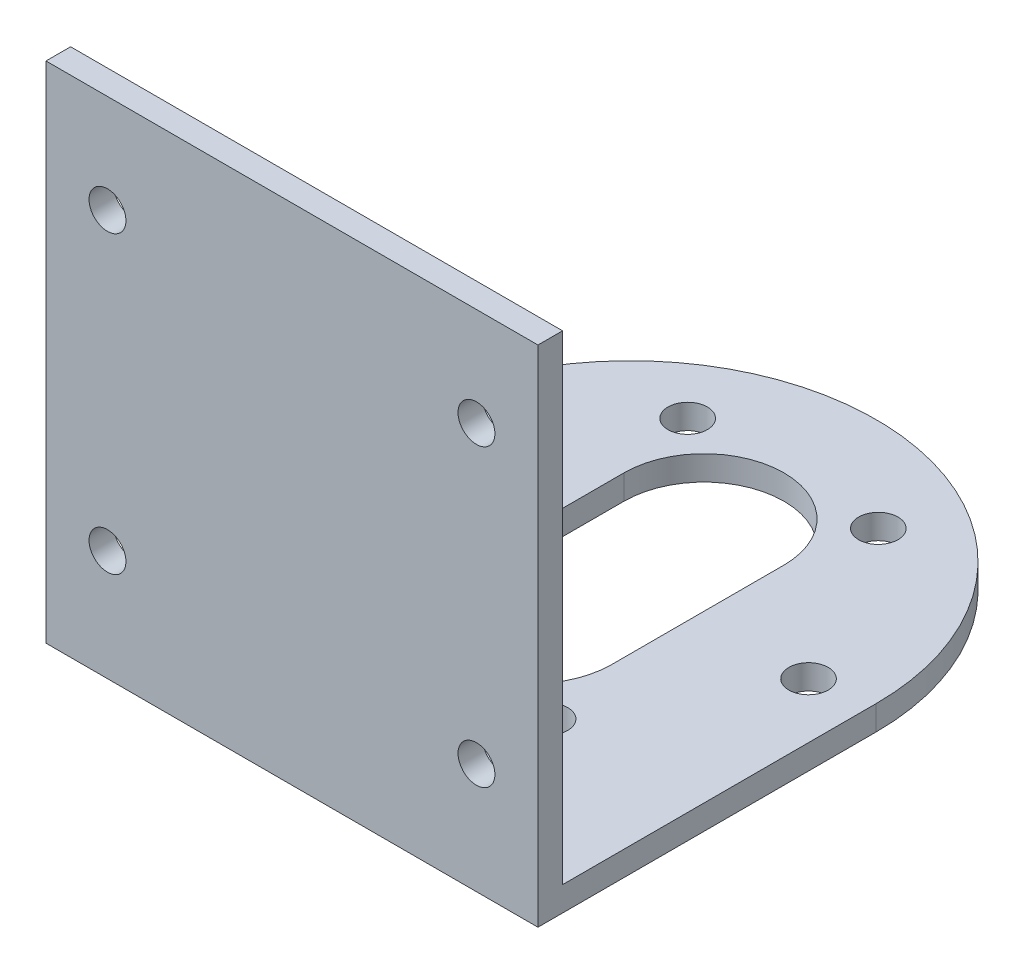
SolidWorks part; units mm, degrees
ref_plane "前视基准面" through (0, 0, 0) normal (0, 0, 1) x (1, 0, 0)
ref_plane "上视基准面" through (0, 0, 0) normal (0, 1, 0) x (1, 0, 0)
ref_plane "右视基准面" through (0, 0, 0) normal (1, 0, 0) x (0, 0, -1)
sketch "草图1" plane through (0, 0, 0) normal (0, 1, 0) x (1, 0, 0)
  line L0 (-21.9582, -2.1643) -> (-21.9582, -29.6643)
  line L1 (-21.9582, -29.6643) -> (18.0418, -29.6643)
  line L2 (18.0418, -29.6643) -> (18.0418, -2.1643)
  line L3 (-1.9582, 17.8357) -> (-57.1523, 17.8357) construction
  line L4 (5.7918, 10.2591) -> (-9.7082, 10.2591) construction
  line L5 (-9.7082, 10.2591) -> (-17.4582, -3.1643) construction
  line L6 (-17.4582, -3.1643) -> (-9.7082, -16.5877) construction
  line L7 (-9.7082, -16.5877) -> (5.7918, -16.5877) construction
  line L8 (5.7918, -16.5877) -> (13.5418, -3.1643) construction
  line L9 (13.5418, -3.1643) -> (5.7918, 10.2591) construction
  line L10 (-1.9582, 3.8357) -> (-1.9582, -10.1643) construction
  line L11 (4.5418, 3.8357) -> (4.5418, -10.1643)
  line L12 (-8.4582, 3.8357) -> (-8.4582, -10.1643)
  arc A0 (18.0418, -2.1643) -> (-21.9582, -2.1643) centre (-1.9582, -2.1643) ccw
  circle A20 centre (-1.9582, -3.1643) radius 15.5 construction
  circle A21 centre (-9.7082, 10.2591) radius 1.6
  circle A22 centre (-17.4582, -3.1643) radius 1.6
  circle A23 centre (-9.7082, -16.5877) radius 1.6
  circle A24 centre (5.7918, -16.5877) radius 1.6
  circle A25 centre (13.5418, -3.1643) radius 1.6
  circle A26 centre (5.7918, 10.2591) radius 1.6
  arc A27 (4.5418, 3.8357) -> (-8.4582, 3.8357) centre (-1.9582, 3.8357) ccw
  arc A28 (-8.4582, -10.1643) -> (4.5418, -10.1643) centre (-1.9582, -10.1643) ccw
  point P10 (-1.9582, -29.6643)
  point P23 (-1.9582, -3.1643)
  dimension "D1" = 40
  dimension "D3" = 31
  dimension "D4" = 26.5
  dimension "D5" = 3.2
  dimension "D6" = 6.5
  dimension "D2" = 47.5
  dimension "D7" = 19.5
extrude "凸台-拉伸1" add sketch "草图1" along normal blind 2
sketch "草图2" plane through (0, 2, 0) normal (0, 1, 0) x (1, 0, 0)
  line L0 (18.0418, -29.6643) -> (18.0418, -2.1643) construction
  line L1 (-21.9582, -29.6643) -> (18.0418, -29.6643)
  line L2 (-21.9582, -29.6643) -> (-21.9582, -27.6643)
  line L3 (-21.9582, -27.6643) -> (18.0418, -27.6643)
  line L4 (18.0418, -29.6643) -> (18.0418, -27.6643)
  dimension "D1" = 2
extrude "凸台-拉伸2" add sketch "草图2" along normal blind 39
sketch "草图3" plane through (0, 0, 27.6643) normal (0, 0, -1) x (-1, 0, 0)
  line L0 (-13.0418, 33) -> (-13.0418, 9) construction
  line L1 (-13.0418, 9) -> (16.9582, 9) construction
  line L2 (16.9582, 9) -> (16.9582, 33) construction
  line L3 (1.9582, 9) -> (1.9582, 2) construction
  line L4 (21.9582, 2) -> (-18.0418, 2) construction
  line L5 (-18.0418, 41) -> (21.9582, 41) construction
  circle A0 centre (-13.0418, 33) radius 1.5
  circle A1 centre (-13.0418, 9) radius 1.5
  circle A2 centre (16.9582, 33) radius 1.5
  circle A3 centre (16.9582, 9) radius 1.5
  dimension "D3" = 3
  dimension "D1" = 24
  dimension "D2" = 30
  dimension "D4" = 8
extrude "切除-拉伸1" cut sketch "草图3" against normal through all
